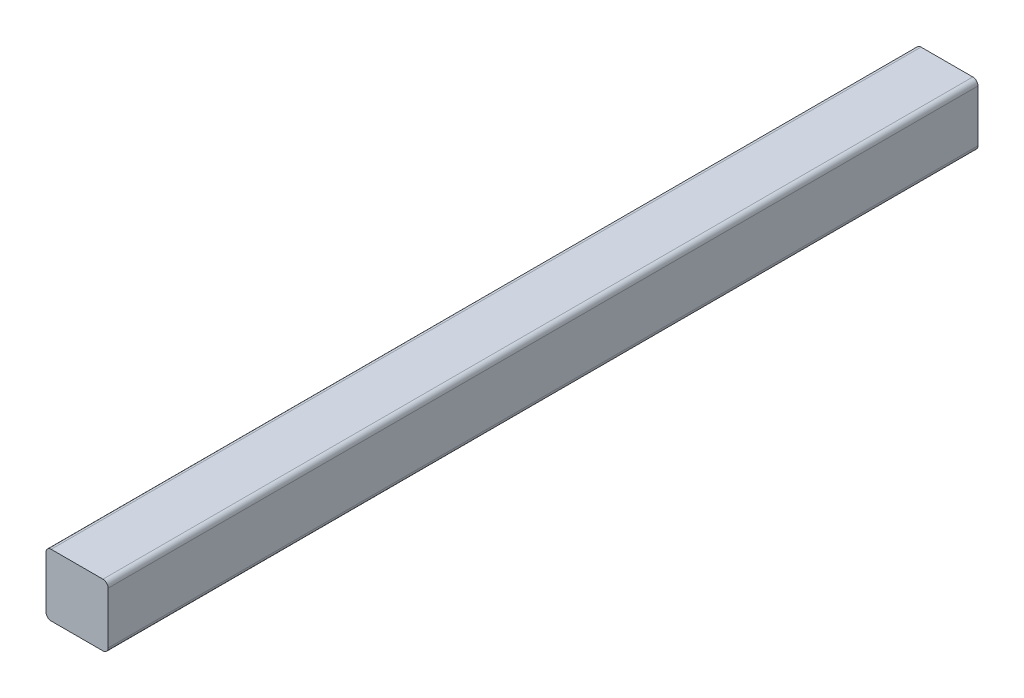
SolidWorks part; units mm, degrees
ref_plane "Front Plane" through (0, 0, 0) normal (0, 0, 1) x (1, 0, 0)
ref_plane "Top Plane" through (0, 0, 0) normal (0, 1, 0) x (1, 0, 0)
ref_plane "Right Plane" through (0, 0, 0) normal (1, 0, 0) x (0, 0, -1)
sketch "Sketch1" plane through (0, 0, 0) normal (0, 0, 1) x (1, 0, 0)
  line L1 (-19.05, -19.05) -> (19.05, -19.05)
  line L2 (-19.05, -19.05) -> (-19.05, 19.05)
  line L3 (-19.05, 19.05) -> (19.05, 19.05)
  line L4 (19.05, -19.05) -> (19.05, 19.05)
  line L5 (-19.05, -19.05) -> (19.05, 19.05) construction
  line L6 (-19.05, 19.05) -> (19.05, -19.05) construction
  point P0 (0, 0)
  dimension "D1" = 38.1
  dimension "D2" = 38.1
extrude "Boss-Extrude1" add sketch "Sketch1" along normal blind 533.4
fillet "Fillet1" radius 3.175 4 edges at (-19.05, 19.05, 266.7) (-19.05, -19.05, 266.7) (19.05, -19.05, 266.7) (19.05, 19.05, 266.7)
